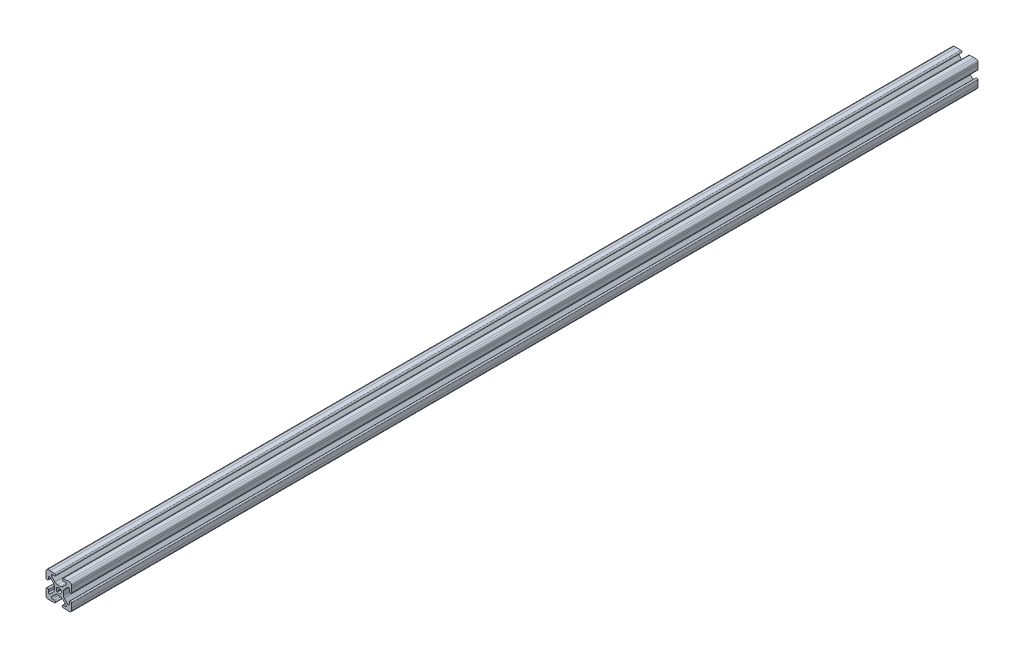
SolidWorks part; units mm, degrees
ref_plane "Front Plane" through (0, 0, 0) normal (0, 0, 1) x (1, 0, 0)
ref_plane "Top Plane" through (0, 0, 0) normal (0, 1, 0) x (1, 0, 0)
ref_plane "Right Plane" through (0, 0, 0) normal (1, 0, 0) x (0, 0, -1)
sketch "Model" plane through (0, 0, 0) normal (0, 0, 1) x (1, 0, 0)
  line L38 (50.6495, 75.4336) -> (50.2699, 75.4336)
  line L39 (50.2699, 75.4336) -> (50.2699, 75.8133)
  line L40 (50.66, 72.9999) -> (53.7746, 72.9999)
  line L41 (56.0196, 72.0699) -> (59.2642, 68.8254)
  line L42 (58.5103, 67.0916) -> (56.5725, 67.1592)
  line L43 (56.498, 65.0269) -> (60.6773, 64.881)
  line L44 (60.6773, 64.881) -> (62.7107, 64.881)
  line L45 (64.7173, 66.8876) -> (64.7173, 68.921)
  line L46 (64.7173, 68.921) -> (64.5713, 73.1002)
  line L47 (62.439, 73.0257) -> (62.5067, 71.0879)
  line L48 (60.7729, 70.334) -> (57.5283, 73.5786)
  line L49 (56.5984, 75.8237) -> (56.5984, 78.9383)
  line L50 (57.5283, 81.1833) -> (60.7729, 84.4279)
  line L51 (62.5067, 83.674) -> (62.439, 81.7362)
  line L52 (64.5713, 81.6617) -> (64.7173, 85.841)
  line L53 (64.7173, 85.841) -> (64.7173, 87.8744)
  line L54 (62.7107, 89.881) -> (60.6773, 89.881)
  line L55 (60.6773, 89.881) -> (56.498, 89.735)
  line L56 (56.5725, 87.6027) -> (58.5103, 87.6704)
  line L57 (59.2642, 85.9366) -> (56.0196, 82.692)
  line L58 (53.7746, 81.7621) -> (50.66, 81.7621)
  line L59 (48.4149, 82.692) -> (45.1703, 85.9366)
  line L60 (45.9242, 87.6704) -> (47.862, 87.6027)
  line L61 (47.9365, 89.735) -> (43.7573, 89.881)
  line L62 (43.7573, 89.881) -> (41.7239, 89.881)
  line L63 (39.7173, 87.8744) -> (39.7173, 85.841)
  line L64 (39.7173, 85.841) -> (39.8632, 81.6617)
  line L65 (41.9955, 81.7362) -> (41.9278, 83.674)
  line L66 (43.6616, 84.4279) -> (46.9062, 81.1833)
  line L67 (47.8361, 78.9383) -> (47.8361, 75.8237)
  line L68 (46.9062, 73.5786) -> (43.6616, 70.334)
  line L69 (41.9278, 71.0879) -> (41.9955, 73.0257)
  line L70 (39.8632, 73.1002) -> (39.7173, 68.921)
  line L71 (39.7173, 68.921) -> (39.7173, 66.8876)
  line L72 (41.7239, 64.881) -> (43.7573, 64.881)
  line L73 (43.7573, 64.881) -> (47.9365, 65.0269)
  line L74 (47.862, 67.1592) -> (45.9242, 67.0916)
  line L75 (45.1703, 68.8254) -> (48.4149, 72.0699)
  arc A29 (50.6495, 75.4336) -> (50.2699, 75.8133) centre (52.2173, 77.381) ccw
  arc A30 (56.0196, 72.0699) -> (53.7746, 72.9999) centre (53.7746, 69.8249) ccw
  arc A31 (58.5103, 67.0916) -> (59.2642, 68.8254) centre (58.5458, 68.1069) ccw
  arc A32 (56.5725, 67.1592) -> (56.498, 65.0269) centre (56.5353, 66.0931) ccw
  arc A33 (62.7107, 64.881) -> (64.7173, 66.8876) centre (62.7107, 66.8876) ccw
  arc A34 (64.5713, 73.1002) -> (62.439, 73.0257) centre (63.5052, 73.063) ccw
  arc A35 (60.7729, 70.334) -> (62.5067, 71.0879) centre (61.4913, 71.0525) ccw
  arc A36 (56.5984, 75.8237) -> (57.5283, 73.5786) centre (59.7734, 75.8237) ccw
  arc A37 (57.5283, 81.1833) -> (56.5984, 78.9383) centre (59.7734, 78.9383) ccw
  arc A38 (62.5067, 83.674) -> (60.7729, 84.4279) centre (61.4913, 83.7095) ccw
  arc A39 (62.439, 81.7362) -> (64.5713, 81.6617) centre (63.5052, 81.699) ccw
  arc A40 (64.7173, 87.8744) -> (62.7107, 89.881) centre (62.7107, 87.8744) ccw
  arc A41 (56.498, 89.735) -> (56.5725, 87.6027) centre (56.5353, 88.6689) ccw
  arc A42 (59.2642, 85.9366) -> (58.5103, 87.6704) centre (58.5458, 86.655) ccw
  arc A43 (53.7746, 81.7621) -> (56.0196, 82.692) centre (53.7746, 84.9371) ccw
  arc A44 (48.4149, 82.692) -> (50.66, 81.7621) centre (50.66, 84.9371) ccw
  arc A45 (45.9242, 87.6704) -> (45.1703, 85.9366) centre (45.8887, 86.655) ccw
  arc A46 (47.862, 87.6027) -> (47.9365, 89.735) centre (47.8993, 88.6689) ccw
  arc A47 (41.7239, 89.881) -> (39.7173, 87.8744) centre (41.7239, 87.8744) ccw
  arc A48 (39.8632, 81.6617) -> (41.9955, 81.7362) centre (40.9293, 81.699) ccw
  arc A49 (43.6616, 84.4279) -> (41.9278, 83.674) centre (42.9432, 83.7095) ccw
  arc A50 (47.8361, 78.9383) -> (46.9062, 81.1833) centre (44.6611, 78.9383) ccw
  arc A51 (46.9062, 73.5786) -> (47.8361, 75.8237) centre (44.6611, 75.8237) ccw
  arc A52 (41.9278, 71.0879) -> (43.6616, 70.334) centre (42.9432, 71.0525) ccw
  arc A53 (41.9955, 73.0257) -> (39.8632, 73.1002) centre (40.9293, 73.063) ccw
  arc A54 (39.7173, 66.8876) -> (41.7239, 64.881) centre (41.7239, 66.8876) ccw
  arc A55 (47.9365, 65.0269) -> (47.862, 67.1592) centre (47.8993, 66.0931) ccw
  arc A56 (45.1703, 68.8254) -> (45.9242, 67.0916) centre (45.8887, 68.1069) ccw
  arc A57 (50.66, 72.9999) -> (48.4149, 72.0699) centre (50.66, 69.8249) ccw
extrude "Boss-Extrude1" add sketch "Model" along normal blind 882.65
